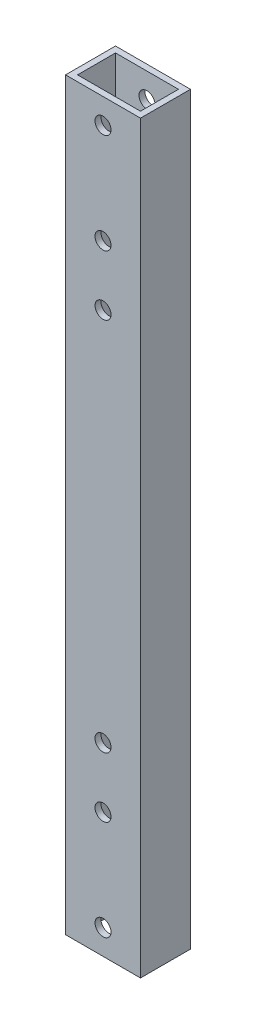
SolidWorks part; units mm, degrees
ref_plane "正面" through (0, 0, 0) normal (0, 0, 1) x (1, 0, 0)
ref_plane "平面" through (0, 0, 0) normal (0, 1, 0) x (1, 0, 0)
ref_plane "右側面" through (0, 0, 0) normal (1, 0, 0) x (0, 0, -1)
sketch "ｽｹｯﾁ1" plane through (0, 0, 0) normal (0, 1, 0) x (1, 0, 0)
  line L0 (-6.3, 3.8) -> (6.3, 3.8)
  line L5 (-7.5, 5) -> (7.5, 5)
  line L6 (-7.5, 5) -> (-7.5, -5)
  line L12 (-7.5, -5) -> (7.5, -5)
  line L13 (7.5, 5) -> (7.5, -5)
  line L14 (-7.5, 5) -> (7.5, -5) construction
  line L15 (-7.5, -5) -> (7.5, 5) construction
  line L16 (6.3, 3.8) -> (6.3, -3.8)
  line L17 (-6.3, -3.8) -> (6.3, -3.8)
  line L18 (-6.3, 3.8) -> (-6.3, -3.8)
  point P0 (0, 0)
  dimension "D1" = 10
  dimension "D2" = 15
  dimension "D3" = 1.2
extrude "ﾎﾞｽ - 押し出し1" add sketch "ｽｹｯﾁ1" along normal mid plane 149.02
sketch "ｽｹｯﾁ3" plane through (0, 0, 5) normal (0, 0, 1) x (1, 0, 0)
  line L0 (0, 74.51) -> (0, 69.51) construction
  line L1 (-7.5, 74.51) -> (7.5, 74.51) construction
  line L2 (0, 69.51) -> (0, 49.51) construction
  circle A0 centre (0, 49.51) radius 1.6
  circle A1 centre (0, 69.51) radius 1.6
  dimension "D3" = 3.2
  dimension "D4" = 3.2
  dimension "D1" = 5
  dimension "D2" = 20
extrude "ｶｯﾄ - 押し出し1" cut sketch "ｽｹｯﾁ3" against normal blind 10
mirror "ﾐﾗｰ1" about plane through (0, 0, 0) normal (0, 1, 0) of "ｶｯﾄ - 押し出し1"
sketch "ｽｹｯﾁ4" plane through (0, 0, -5) normal (0, 0, -1) x (-1, 0, 0)
  line L0 (0, 0) -> (0, 37.5) construction
  line L1 (0, 0) -> (7.5, 0) construction
  line L2 (7.5, 74.51) -> (7.5, -74.51) construction
  circle A4 centre (0, 37.5) radius 1.6
  circle A5 centre (0, -37.5) radius 1.6
  dimension "D2" = 3.2
  dimension "D1" = 37.5
extrude "ｶｯﾄ - 押し出し2" cut sketch "ｽｹｯﾁ4" against normal blind 10
